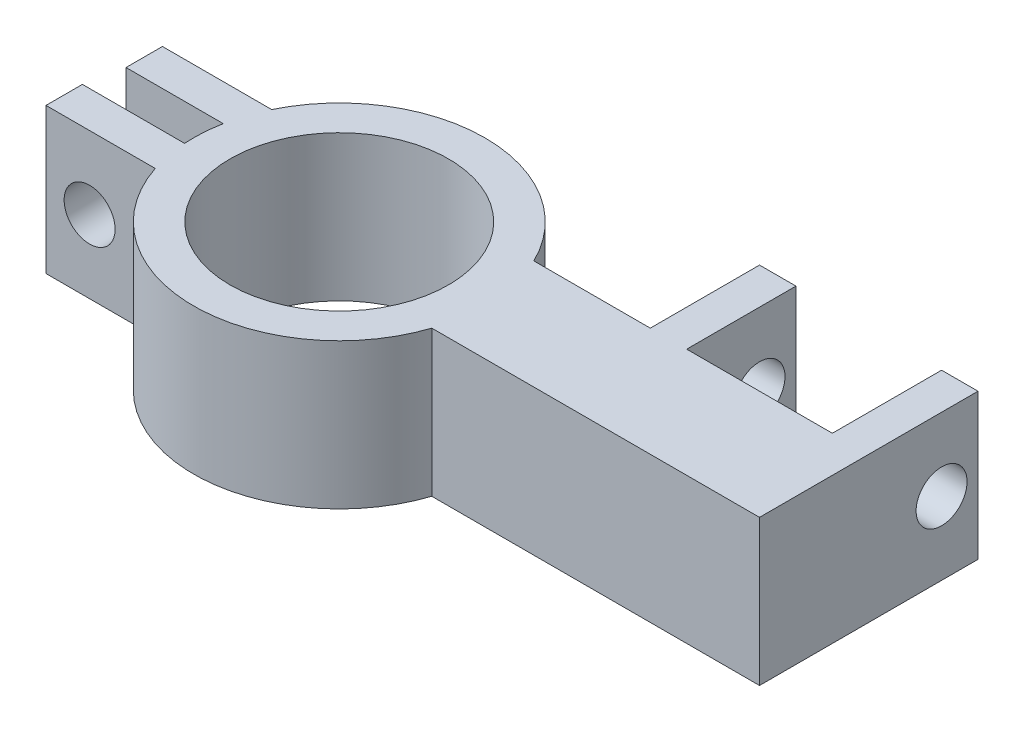
SolidWorks part; units mm, degrees
material "AISI 304"
ref_plane "Front Plane" through (0, 0, 0) normal (0, 0, 1) x (1, 0, 0)
ref_plane "Top Plane" through (0, 0, 0) normal (0, 1, 0) x (1, 0, 0)
ref_plane "Right Plane" through (0, 0, 0) normal (1, 0, 0) x (0, 0, -1)
sketch "Sketch2" plane through (0, 0, 0) normal (0, 1, 0) x (1, 0, 0)
  line L0 (0, 0) -> (0, 30)
  line L1 (0, 30) -> (-5, 30)
  line L2 (-5, 30) -> (-5, 15)
  line L3 (-5, 15) -> (-25, 15)
  line L4 (-25, 15) -> (-25, 30)
  line L5 (-25, 30) -> (-30, 30)
  line L6 (-30, 30) -> (-30, 15)
  line L7 (-30, 15) -> (-45.9877, 15)
  line L8 (0, 0) -> (-45, 0)
  line L11 (-81.9877, 15) -> (-96.9877, 15)
  line L12 (-96.9877, 15) -> (-96.9877, 10)
  line L13 (-96.9877, 10) -> (-83.6391, 10)
  line L14 (-82.9755, 0) -> (-97.9755, 0)
  line L15 (-97.9755, 0) -> (-97.9755, 5)
  line L16 (-97.9755, 5) -> (-83.9466, 5)
  arc A0 (-45.9877, 15) -> (-81.9877, 15) centre (-63.9877, 6.2822) ccw
  circle A2 centre (-63.9877, 6.2822) radius 15
  arc A3 (-82.9755, 0) -> (-45, 0) centre (-63.9877, 6.2822) ccw
  arc A4 (-83.6391, 10) -> (-83.9466, 5) centre (-63.9877, 6.2822) ccw
  point P22 (0, 0)
  dimension "D9" = 40
  dimension "D10" = 30
  dimension "D15" = 33
  dimension "D1" = 20
  dimension "D2" = 5
  dimension "D3" = 5
  dimension "D4" = 30
  dimension "D5" = 15
  dimension "D6" = 15
  dimension "D7" = 30
  dimension "D8" = 45
  dimension "D11" = 15
  dimension "D12" = 5
  dimension "D13" = 5
  dimension "D14" = 15
extrude "Boss-Extrude1" add sketch "Sketch2" against normal blind 20 contours A2 | L7 A0 L11 L12 L13 A4 L16 L15 L14 A3 L8 L0 L1 L2 L3 L4 L5 L6
sketch "Sketch3" plane through (0, 0, 0) normal (1, 0, 0) x (0, 0, -1)
  line L0 (30, -20) -> (30, 0) construction
  line L1 (0, -20) -> (30, -20) construction
  circle A0 centre (25, -10) radius 3.5
  dimension "D1" = 7
  dimension "D2" = 5
  dimension "D3" = 10
extrude "Cut-Extrude1" cut sketch "Sketch3" against normal mid plane 73
cosmetic thread "Cosmetic Thread1" parameters "D1"=24.9999, "D2"=8
cosmetic thread "Cosmetic Thread2" parameters "D1"=24.9999, "D2"=8
sketch "Sketch4" plane through (0, 0, -15) normal (0, 0, -1) x (-1, 0, 0)
  line L0 (81.9877, 0) -> (96.9877, 0) construction
  line L1 (96.9877, -20) -> (96.9877, 0) construction
  circle A0 centre (91.9877, -10) radius 3.5
  dimension "D1" = 7
  dimension "D2" = 10
  dimension "D3" = 5
extrude "Cut-Extrude2" cut sketch "Sketch4" against normal mid plane 73
cosmetic thread "Cosmetic Thread3" parameters "D1"=15, "D2"=8
